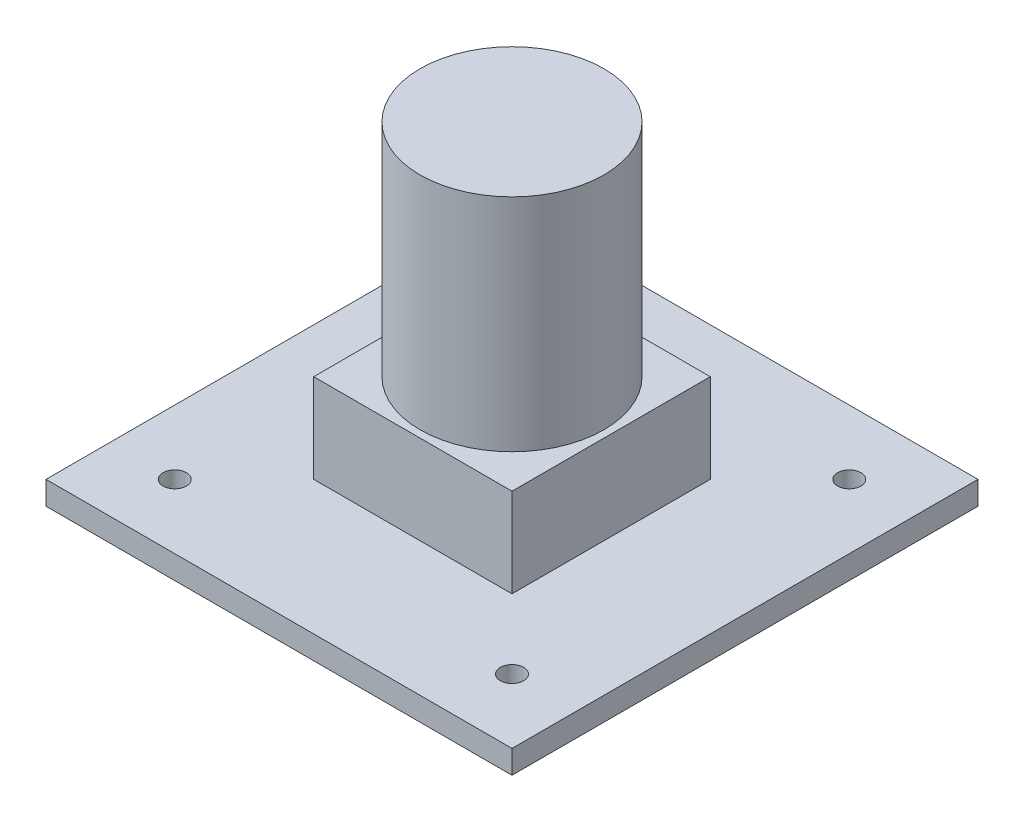
SolidWorks part; units mm, degrees
ref_plane "Front Plane" through (0, 0, 0) normal (0, 0, 1) x (1, 0, 0)
ref_plane "Top Plane" through (0, 0, 0) normal (0, 1, 0) x (1, 0, 0)
ref_plane "Right Plane" through (0, 0, 0) normal (1, 0, 0) x (0, 0, -1)
sketch "Sketch1" plane through (0, 0, 0) normal (0, 1, 0) x (1, 0, 0)
  line L1 (-19, 19) -> (19, 19)
  line L2 (-19, 19) -> (-19, -19)
  line L3 (-19, -19) -> (19, -19)
  line L4 (19, 19) -> (19, -19)
  line L5 (-19, 19) -> (19, -19) construction
  line L6 (-19, -19) -> (19, 19) construction
  point P0 (0, 0)
  dimension "D1" = 38
  dimension "D2" = 38
extrude "Boss-Extrude1" add sketch "Sketch1" along normal blind 1.9
sketch "Sketch2" plane through (0, 1.9, 0) normal (0, 1, 0) x (1, 0, 0)
  line L1 (-8.085, 8.085) -> (8.085, 8.085)
  line L2 (-8.085, 8.085) -> (-8.085, -8.085)
  line L3 (-8.085, -8.085) -> (8.085, -8.085)
  line L4 (8.085, 8.085) -> (8.085, -8.085)
  line L5 (-8.085, 8.085) -> (8.085, -8.085) construction
  line L6 (-8.085, -8.085) -> (8.085, 8.085) construction
  point P0 (0, 0)
  dimension "D1" = 16.17
  dimension "D2" = 16.17
extrude "Boss-Extrude2" add sketch "Sketch2" along normal blind 7.25
sketch "Sketch4" plane through (0, 9.15, 0) normal (0, 1, 0) x (1, 0, 0)
  circle A0 centre (0, 0) radius 7.5
  dimension "D1" = 15
extrude "Boss-Extrude3" add sketch "Sketch4" along normal blind 18
sketch "Sketch5" plane through (0, 1.9, 0) normal (0, 1, 0) x (1, 0, 0)
  line L1 (-13.75, 13.75) -> (13.75, 13.75) construction
  line L2 (-13.75, 13.75) -> (-13.75, -13.75) construction
  line L3 (-13.75, -13.75) -> (13.75, -13.75) construction
  line L4 (13.75, 13.75) -> (13.75, -13.75) construction
  line L5 (-13.75, 13.75) -> (13.75, -13.75) construction
  line L6 (-13.75, -13.75) -> (13.75, 13.75) construction
  circle A0 centre (-13.75, 13.75) radius 0.95
  circle A1 centre (13.75, 13.75) radius 0.95
  circle A2 centre (13.75, -13.75) radius 0.95
  circle A3 centre (-13.75, -13.75) radius 0.95
  point P0 (0, 0)
  dimension "D2" = 1.9
  dimension "D1" = 27.5
extrude "Cut-Extrude1" cut sketch "Sketch5" against normal blind 18
